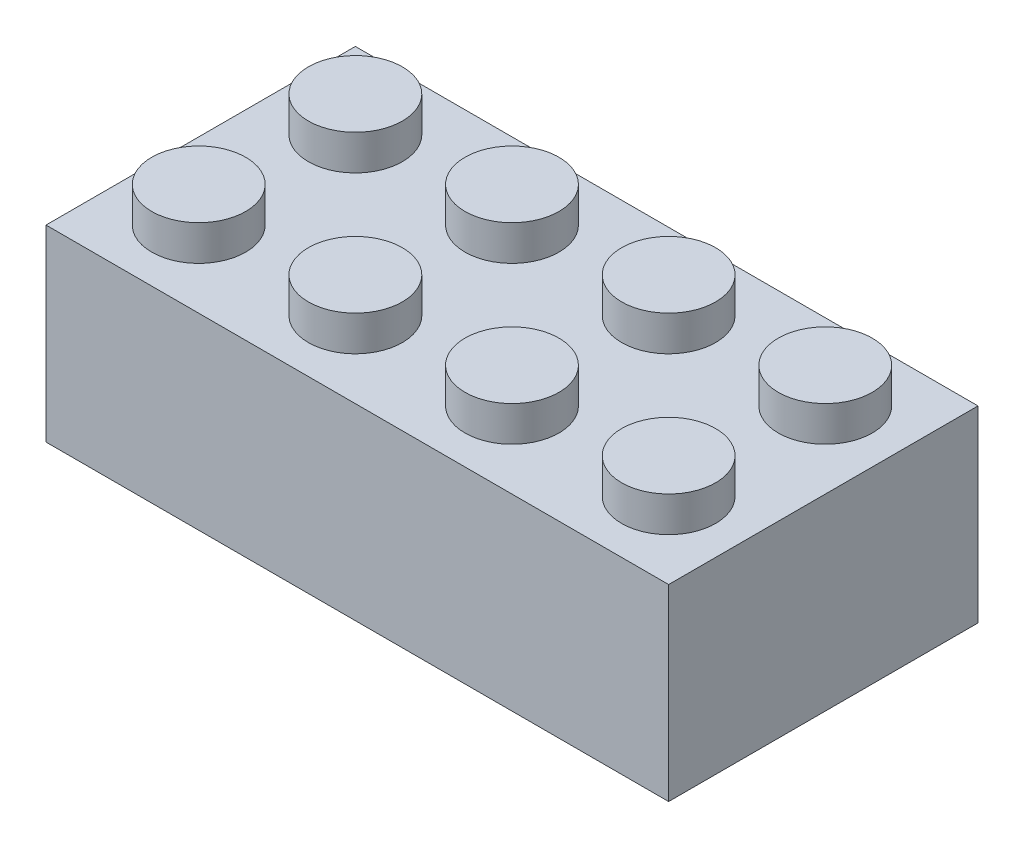
SolidWorks part; units mm, degrees
ref_plane "Front Plane" through (0, 0, 0) normal (0, 0, 1) x (1, 0, 0)
ref_plane "Top Plane" through (0, 0, 0) normal (0, 1, 0) x (1, 0, 0)
ref_plane "Right Plane" through (0, 0, 0) normal (1, 0, 0) x (0, 0, -1)
sketch "Sketch1" plane through (0, 0, 0) normal (0, 1, 0) x (1, 0, 0)
  line L1 (-15.9, 7.9) -> (15.9, 7.9)
  line L2 (-15.9, 7.9) -> (-15.9, -7.9)
  line L3 (-15.9, -7.9) -> (15.9, -7.9)
  line L4 (15.9, 7.9) -> (15.9, -7.9)
  line L5 (-15.9, 7.9) -> (15.9, -7.9) construction
  line L6 (-15.9, -7.9) -> (15.9, 7.9) construction
  point P0 (0, 0)
  dimension "D1" = 31.8
  dimension "D2" = 15.8
extrude "Boss-Extrude1" add sketch "Sketch1" against normal blind 9.6
sketch "Sketch2" plane through (0, 0, 0) normal (0, 1, 0) x (1, 0, 0)
  line L0 (-12, 4) -> (-4, 4) construction
  line L1 (-4, 4) -> (4, 4) construction
  line L2 (4, 4) -> (12, 4) construction
  line L3 (12, 4) -> (12, -4) construction
  circle A0 centre (-12, 4) radius 2.4
  circle A1 centre (-4, 4) radius 2.4
  circle A2 centre (4, 4) radius 2.4
  circle A3 centre (12, 4) radius 2.4
  circle A4 centre (12, -4) radius 2.4
  circle A5 centre (4, -4) radius 2.4
  circle A6 centre (-4, -4) radius 2.4
  circle A7 centre (-12, -4) radius 2.4
  point P16 (0, 4)
  point P17 (12, 0)
  point P18 (0, 0)
  point P19 (0, 0)
  point P20 (0, 0)
  point P21 (0, 0)
  dimension "D1" = 4.8
  dimension "D2" = 8
extrude "Boss-Extrude2" add sketch "Sketch2" along normal blind 1.8
sketch "Sketch3" plane through (0, -9.6, 0) normal (0, -1, 0) x (1, 0, 0)
  line L0 (-15.9, 7.9) -> (15.9, 7.9) construction
  line L1 (-14.7, 6.7) -> (14.7, 6.7)
  line L2 (-14.7, 6.7) -> (-14.7, -6.7)
  line L3 (-14.7, -6.7) -> (14.7, -6.7)
  line L4 (14.7, 6.7) -> (14.7, -6.7)
  line L5 (-14.7, 6.7) -> (14.7, -6.7) construction
  line L6 (-14.7, -6.7) -> (14.7, 6.7) construction
  line L7 (-15.9, -7.9) -> (-15.9, 7.9) construction
  point P0 (0, 0)
  dimension "D1" = 1.2
  dimension "D2" = 1.2
extrude "Cut-Extrude1" cut sketch "Sketch3" against normal blind 8.6
sketch "Sketch4" plane through (0, -1, 0) normal (0, -1, 0) x (1, 0, 0)
  line L0 (-12, 4) -> (-4, 4) construction
  line L1 (-4, 4) -> (4, 4) construction
  line L2 (4, 4) -> (12, 4) construction
  line L3 (12, 4) -> (12, -4) construction
  circle A0 centre (-12, 4) radius 1.3
  circle A1 centre (-4, 4) radius 1.3
  circle A2 centre (4, 4) radius 1.3
  circle A3 centre (12, 4) radius 1.3
  circle A4 centre (12, -4) radius 1.3
  circle A5 centre (4, -4) radius 1.3
  circle A6 centre (-4, -4) radius 1.3
  circle A7 centre (-12, -4) radius 1.3
  point P16 (0, 4)
  point P17 (12, 0)
  dimension "D2" = 2.6
  dimension "D1" = 8
extrude "Cut-Extrude2" cut sketch "Sketch4" against normal blind 1.7
sketch "Sketch5" plane through (0, -1, 0) normal (0, -1, 0) x (1, 0, 0)
  line L0 (-8, 0) -> (0, 0) construction
  line L1 (0, 0) -> (8, 0) construction
  circle A0 centre (0, 0) radius 2.4
  circle A1 centre (8, 0) radius 2.4
  circle A2 centre (-8, 0) radius 2.4
  circle A3 centre (-8, 0) radius 3.11
  circle A4 centre (0, 0) radius 3.11
  circle A5 centre (8, 0) radius 3.11
  dimension "D2" = 4.8
  dimension "D1" = 8
  dimension "D3" = 0.71
extrude "Boss-Extrude3" add sketch "Sketch5" along normal up to surface (8.6 mm away) up to face at (0, -9.6, 0)
sketch "Sketch6" plane through (0, -1, 0) normal (0, -1, 0) x (1, 0, 0)
  line L0 (-0.4, 6.7) -> (-0.4, 3.0842)
  line L1 (14.7, 6.7) -> (-14.7, 6.7) construction
  line L2 (-0.4, 6.7) -> (0.4, 6.7)
  line L3 (14.7, 6.7) -> (-14.7, 6.7) construction
  line L4 (0.4, 6.7) -> (0.4, 3.0842)
  line L5 (-0.4, -3.0842) -> (-0.4, -6.7)
  line L6 (-14.7, -6.7) -> (14.7, -6.7) construction
  line L7 (-0.4, -6.7) -> (0.4, -6.7)
  line L8 (-14.7, -6.7) -> (14.7, -6.7) construction
  line L9 (0.4, -6.7) -> (0.4, -3.0842)
  circle A0 centre (0, 0) radius 3.11 construction
  arc A1 (-0.4, 3.0842) -> (0.4, 3.0842) centre (0, 0) cw
  arc A2 (-0.4, -3.0842) -> (0.4, -3.0842) centre (0, 0) ccw
  point P6 (0, 6.7)
  point P22 (0, -6.7)
  dimension "D1" = 0.8
extrude "Boss-Extrude4" add sketch "Sketch6" along normal blind 6.3
sketch "Sketch7" plane through (0, -1, 0) normal (0, -1, 0) x (1, 0, 0)
  line L0 (14.7, 6.7) -> (-14.7, 6.7) construction
  line L1 (-12.3, 6.7) -> (-11.7, 6.7)
  line L2 (-12.3, 6.7) -> (-12.3, 6.5)
  line L3 (-12.3, 6.5) -> (-11.7, 6.5)
  line L4 (-11.7, 6.7) -> (-11.7, 6.5)
  line L5 (-14.7, 6.7) -> (-14.7, -6.7) construction
  line L6 (-4.3, 6.7) -> (-3.7, 6.7)
  line L7 (-4.3, 6.7) -> (-4.3, 6.5)
  line L8 (-4.3, 6.5) -> (-3.7, 6.5)
  line L9 (-3.7, 6.7) -> (-3.7, 6.5)
  line L10 (-14.7, 4.3) -> (-14.5, 4.3)
  line L11 (-14.7, 4.3) -> (-14.7, 3.7)
  line L12 (-14.7, 3.7) -> (-14.5, 3.7)
  line L13 (-14.5, 4.3) -> (-14.5, 3.7)
  point P16 (-14.5, 4)
  point P17 (-12, 6.5)
  point P18 (-4, 6.5)
  dimension "D1" = 0.6
  dimension "D2" = 0.2
extrude "Boss-Extrude5" add sketch "Sketch7" along normal up to surface (8.6 mm away) up to face at (0, -9.6, 0)
mirror "Mirror1" about plane through (0, 0, 0) normal (1, 0, 0) of "Boss-Extrude5"
mirror "Mirror2" about plane through (0, 0, 0) normal (0, 0, 1) of "Mirror1", "Boss-Extrude5"
equation "\"D2@Sketch3\"=\"D1@Sketch3\""
